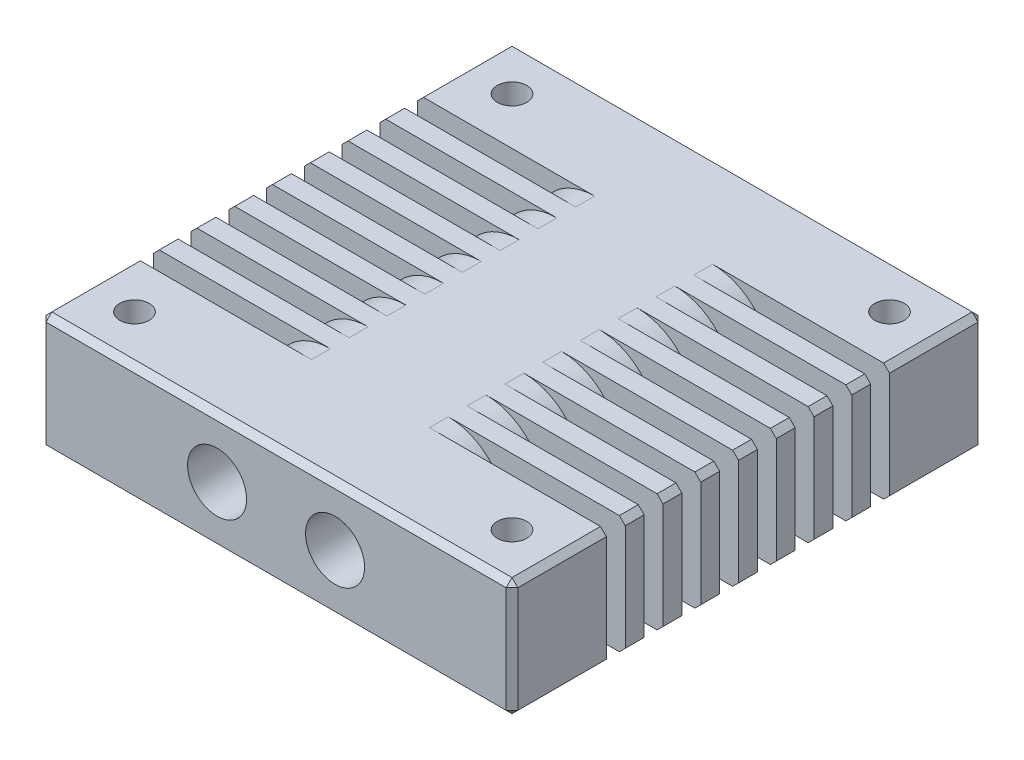
SolidWorks part; units mm, degrees
ref_plane "Plan de face" through (0, 0, 0) normal (0, 0, 1) x (1, 0, 0)
ref_plane "Plan de dessus" through (0, 0, 0) normal (0, 1, 0) x (1, 0, 0)
ref_plane "Plan de droite" through (0, 0, 0) normal (1, 0, 0) x (0, 0, -1)
sketch "Esquisse2" plane through (0, 0, 0) normal (0, 0, 1) x (1, 0, 0)
  line L1 (0, 0) -> (40, 0)
  line L2 (0, 0) -> (0, 10)
  line L3 (0, 10) -> (40, 10)
  line L4 (40, 0) -> (40, 10)
  dimension "D1" = 10
  dimension "D2" = 40
extrude "Boss.-Extru.1" add sketch "Esquisse2" along normal blind 40
sketch "Esquisse5" plane through (0, 0, 40) normal (0, 0, 1) x (1, 0, 0)
  line L0 (40, 0) -> (40, 10) construction
  line L1 (40, 10) -> (0, 10) construction
  circle A0 centre (25, 5) radius 2
  dimension "D1" = 4
  dimension "D2" = 15
  dimension "D3" = 5
hole_wizard "Diamètre du perçage Ø4.1 (4.1)1" positions "Esquisse7" profile "Esquisse6" hole size "Ø4.1" standard "ISO" end condition through all
sketch "Esquisse7" plane through (0, 0, 40) normal (0, 0, 1) x (1, 0, 0)
  point P0 (25, 5)
sketch "Esquisse6" plane through (25, 5, 40) normal (1, 0, 0) x (0, -1, 0)
  line L0 (0, 0) -> (0, 40)
  line L1 (0, 40) -> (2.05, 40)
  line L2 (2.05, 40) -> (2.05, 0)
  line L5 (2.05, 0) -> (0, 0)
  line L11 (0, -6.35) -> (0, 107.95) construction
  dimension "Diamètre du perçage jusqu'au prochain" = 4.1
  dimension "Profondeur du perçage jusqu'au prochain" = 40
hole_wizard "Trou pour taraudage pour trou taraudé M61" positions "Esquisse10" profile "Esquisse9" hole size "M6" standard "ISO"
sketch "Esquisse10" plane through (0, 0, 40) normal (0, 0, 1) x (1, 0, 0)
  point P0 (25, 5)
sketch "Esquisse9" plane through (25, 5, 40) normal (1, 0, 0) x (0, -1, 0)
  line L0 (0, 0) -> (0, 9.5022)
  line L1 (0, 9.5022) -> (2.5, 8)
  line L2 (2.5, 8) -> (2.5, 0)
  line L5 (2.5, 0) -> (0, 0)
  line L10 (0, 9.5022) -> (-2.5, 8) construction
  line L11 (0, -6.35) -> (0, 107.95) construction
  dimension "Diamètre du perçage" = 5
  dimension "Profondeur du perçage" = 8
  dimension "Angle de pointe" = 118
hole_wizard "Diamètre du perçage Ø6.0 (6)1" positions "Esquisse14" profile "Esquisse13" hole size "Ø6.0" standard "ISO"
sketch "Esquisse14" plane through (0, 0, 0) normal (0, 0, -1) x (-1, 0, 0)
  point P0 (-25, 5)
sketch "Esquisse13" plane through (25, 5, 0) normal (1, 0, 0) x (0, 1, 0)
  line L0 (0, 0) -> (0, 21.8026)
  line L1 (0, 21.8026) -> (3, 20)
  line L2 (3, 20) -> (3, 0)
  line L5 (3, 0) -> (0, 0)
  line L10 (0, 21.8026) -> (-3, 20) construction
  line L11 (0, -6.35) -> (0, 107.95) construction
  dimension "Diamètre du perçage" = 6
  dimension "Profondeur du perçage" = 20
  dimension "Angle de pointe" = 118
sketch "Esquisse15" plane through (0, 0, 0) normal (0, -1, 0) x (1, 0, 0)
  line L0 (0, 40) -> (40, 40) construction
  line L1 (0, 40) -> (0, 0) construction
  line L2 (40, 40) -> (40, 0) construction
  line L3 (0, 0) -> (40, 0) construction
  circle A0 centre (4, 36) radius 1.5
  circle A1 centre (36, 36) radius 1.5
  circle A2 centre (36, 4) radius 1.5
  circle A3 centre (4, 4) radius 1.5
  circle A4 centre (25, 4) radius 1.5
  dimension "D1" = 3
  dimension "D2" = 3
  dimension "D3" = 3
  dimension "D4" = 3
  dimension "D5" = 3
  dimension "D14" = 4
  dimension "D6" = 4
  dimension "D7" = 4
  dimension "D8" = 4
  dimension "D9" = 4
  dimension "D10" = 4
  dimension "D11" = 4
  dimension "D12" = 4
  dimension "D13" = 4
  dimension "D15" = 25
hole_wizard "Trou pour taraudage pour trou taraudé M32" positions "Esquisse17" profile "Esquisse16" hole size "M3" standard "ISO" end condition through all
sketch "Esquisse17" plane through (0, 0, 0) normal (0, -1, 0) x (-1, 0, 0)
  point P0 (-4, -36)
  point P3 (-36, -36)
  point P6 (-36, -4)
  point P9 (-4, -4)
sketch "Esquisse16" plane through (4, 0, 36) normal (1, 0, 0) x (0, 0, -1)
  line L0 (0, 0) -> (0, 10)
  line L1 (0, 10) -> (1.25, 10)
  line L2 (1.25, 10) -> (1.25, 0)
  line L5 (1.25, 0) -> (0, 0)
  line L11 (0, -6.35) -> (0, 107.95) construction
  dimension "Diamètre du perçage jusqu'au prochain" = 2.5
  dimension "Profondeur du perçage jusqu'au prochain" = 10
hole_wizard "Trou pour taraudage pour trou taraudé M31" positions "Esquisse19" profile "Esquisse18" hole size "M3" standard "ISO"
sketch "Esquisse19" plane through (0, 0, 0) normal (0, -1, 0) x (-1, 0, 0)
  point P0 (-25, -4)
sketch "Esquisse18" plane through (25, 0, 4) normal (1, 0, 0) x (0, 0, -1)
  line L0 (0, 0) -> (0, 5.7511)
  line L1 (0, 5.7511) -> (1.25, 5)
  line L2 (1.25, 5) -> (1.25, 0)
  line L5 (1.25, 0) -> (0, 0)
  line L10 (0, 5.7511) -> (-1.25, 5) construction
  line L11 (0, -6.35) -> (0, 107.95) construction
  dimension "Diamètre du perçage" = 2.5
  dimension "Profondeur du perçage" = 5
  dimension "Angle de pointe" = 118
chamfer "Chanfrein1" distance 0.5 angle 45 12 edges at (40, 5, 0) (20, 10, 0) (0, 5, 0) (20, 0, 0) (40, 10, 20) (40, 0, 20) (0, 10, 20) (0, 0, 20) (0, 5, 40) (20, 10, 40) (40, 5, 40) (20, 0, 40)
pattern_linear "Répétition linéaire2" count 2 spacing 10 along (-1, 0, 0) of "Trou pour taraudage pour trou taraudé M31", "Diamètre du perçage Ø6.0 (6)1", "Trou pour taraudage pour trou taraudé M61", "Diamètre du perçage Ø4.1 (4.1)1"
sketch "Esquisse20" plane through (0, 40, 40) normal (0, 0, -1) x (-1, 0, 0)
  line L0 (-15, -35) -> (-25, -35) construction
  line L1 (-15, -40) -> (-25, -40)
  line L3 (-15, -30) -> (-25, -30)
  arc A0 (-15, -40) -> (-15, -30) centre (-15, -35) ccw
  circle A1 centre (-20, -35) radius 30.0561
  arc A2 (-25, -30) -> (-25, -40) centre (-25, -35) ccw
  point P3 (-20, -35)
  dimension "D1" = 5
  dimension "D2" = 5
  dimension "D3" = 10
extrude "Enlèv. mat.-Extru.1" cut sketch "Esquisse20" along normal blind 1.6 from offset 8
pattern_linear "Répétition linéaire1" count 8 spacing 3.2 along (0, 0, -1) of "Enlèv. mat.-Extru.1"
